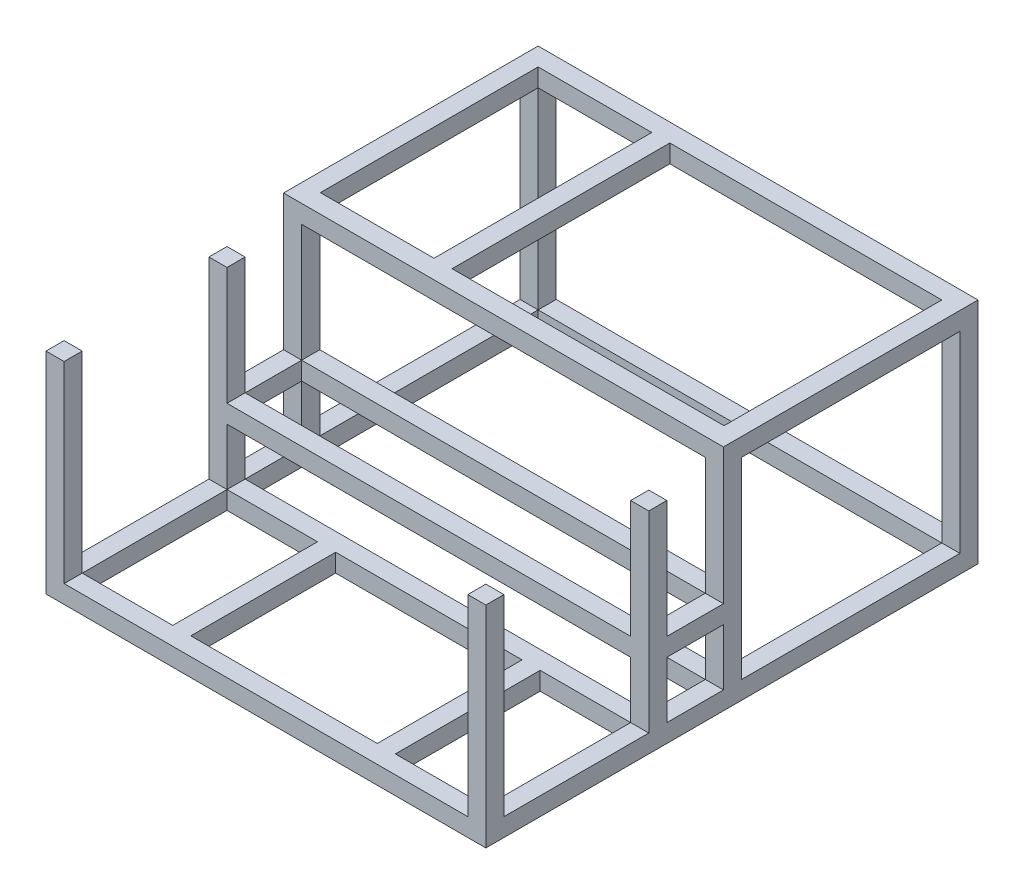
SolidWorks part; units mm, degrees
ref_plane "Front Plane" through (0, 0, 0) normal (0, 0, 1) x (1, 0, 0)
ref_plane "Top Plane" through (0, 0, 0) normal (0, 1, 0) x (1, 0, 0)
ref_plane "Right Plane" through (0, 0, 0) normal (1, 0, 0) x (0, 0, -1)
sketch "Sketch1" plane through (0, 0, 0) normal (1, 0, 0) x (0, 0, -1)
  line L0 (-359.5886, 0) -> (330.9739, 0)
  line L1 (330.9739, 0) -> (330.9739, -320.675)
  line L2 (330.9739, -320.675) -> (-359.5886, -320.675)
  line L3 (-359.5886, -320.675) -> (-359.5886, 0)
  line L4 (-334.1886, -25.4) -> (-334.1886, -295.275)
  line L5 (-334.1886, -295.275) -> (305.5739, -295.275)
  line L6 (305.5739, -295.275) -> (305.5739, -25.4)
  line L7 (305.5739, -25.4) -> (-334.1886, -25.4)
  line L8 (-130.9886, -25.4) -> (-130.9886, -295.275)
  line L9 (-130.9886, -295.275) -> (-105.5886, -295.275)
  line L10 (-105.5886, -295.275) -> (-105.5886, -25.4)
  line L11 (-105.5886, -25.4) -> (-130.9886, -25.4)
  line L12 (-26.2136, -25.4) -> (-26.2136, -295.275)
  line L13 (-26.2136, -295.275) -> (-0.8136, -295.275)
  line L14 (-0.8136, -295.275) -> (-0.8136, -25.4)
  line L15 (-0.8136, -25.4) -> (-26.2136, -25.4)
  line L16 (-105.5886, -190.5) -> (-26.2136, -190.5)
  line L17 (-26.2136, -190.5) -> (-26.2136, -215.9)
  line L18 (-26.2136, -215.9) -> (-105.5886, -215.9)
  line L19 (-105.5886, -215.9) -> (-105.5886, -190.5)
  dimension "D1" = 690.5625
  dimension "D2" = 320.675
  dimension "D3" = 25.4
  dimension "D4" = 25.4
  dimension "D5" = 25.4
  dimension "D6" = 25.4
  dimension "D7" = 25.4
  dimension "D8" = 25.4
  dimension "D9" = 25.4
  dimension "D10" = 254
  dimension "D11" = 358.775
  dimension "D12" = 130.175
extrude "Boss-Extrude1" add sketch "Sketch1" along normal blind 617.22 contours L3 L2 L1 L0 L7 L6 L5 L4 | L5 L14 L7 L12 | L8 L9 L10 L11 | L16 L17 L18 L19
sketch "Sketch2" plane through (0, 0, 359.5886) normal (0, 0, 1) x (1, 0, 0)
  line L0 (25.4, -25.4) -> (25.4, -295.275)
  line L1 (25.4, -295.275) -> (591.82, -295.275)
  line L2 (591.82, -295.275) -> (591.82, -25.4)
  line L3 (591.82, -25.4) -> (25.4, -25.4)
  line L4 (0, -320.675) -> (0, 0) construction
  line L5 (617.22, 0) -> (0, 0) construction
  line L6 (617.22, -320.675) -> (0, -320.675) construction
  line L7 (617.22, -320.675) -> (617.22, 0) construction
  dimension "D1" = 25.4
  dimension "D2" = 25.4
  dimension "D3" = 25.4
  dimension "D4" = 25.4
extrude "Cut-Extrude1" cut sketch "Sketch2" against normal through all
sketch "Sketch3" plane through (0, -190.5, 0) normal (0, 1, 0) x (1, 0, 0)
sketch "Sketch4" plane through (25.4, 0, 0) normal (1, 0, 0) x (0, 0, -1)
  line L0 (-26.2136, -190.5) -> (-0.8136, -190.5)
  line L1 (-0.8136, -295.275) -> (-0.8136, -25.4) construction
  line L2 (-0.8136, -190.5) -> (-0.8136, -215.8777)
  line L3 (-0.8136, -215.8777) -> (-130.9886, -215.8777)
  line L4 (-130.9886, -25.4) -> (-130.9886, -295.275) construction
  line L5 (-130.9886, -215.8777) -> (-130.9886, -190.5)
  line L6 (-130.9886, -190.5) -> (-26.2136, -190.5)
extrude "Boss-Extrude2" add sketch "Sketch4" along normal blind 566.42
sketch "Sketch6" plane through (0, -190.5, 0) normal (0, 1, 0) x (1, 0, 0)
  line L0 (591.82, -105.5886) -> (25.4, -105.5886)
  line L1 (25.4, -105.5886) -> (25.4, -26.2136)
  line L2 (25.4, -26.2136) -> (591.82, -26.2136)
  line L3 (591.82, -26.2136) -> (591.82, -105.5886)
extrude "Cut-Extrude2" cut sketch "Sketch6" against normal up to next
sketch "Sketch7" plane through (0, -295.275, 0) normal (0, 1, 0) x (1, 0, 0)
  line L0 (591.82, -334.1886) -> (591.82, -130.9886)
  line L1 (591.82, -130.9886) -> (464.82, -130.9886)
  line L2 (464.82, -130.9886) -> (464.82, -334.1886)
  line L3 (464.82, -334.1886) -> (591.82, -334.1886)
  line L4 (617.22, -334.1886) -> (617.22, -130.9886) construction
  line L5 (308.61, -359.5886) -> (308.61, 583.7712) construction
  line L6 (25.4, -359.5886) -> (591.82, -359.5886) construction
  line L7 (152.4, -130.9886) -> (152.4, -334.1886)
  line L8 (25.4, -130.9886) -> (152.4, -130.9886)
  line L9 (25.4, -334.1886) -> (25.4, -130.9886)
  line L10 (152.4, -334.1886) -> (25.4, -334.1886)
  line L11 (177.8, -334.1886) -> (177.8, -130.9886)
  line L12 (177.8, -130.9886) -> (439.42, -130.9886)
  line L13 (439.42, -130.9886) -> (439.42, -334.1886)
  line L14 (439.42, -334.1886) -> (177.8, -334.1886)
  dimension "D1" = 152.4
  dimension "D2" = 25.4
  dimension "D3" = 25.4
extrude "Cut-Extrude3" cut sketch "Sketch7" against normal through all
sketch "Sketch8" plane through (0, 0, 0) normal (0, 1, 0) x (1, 0, 0)
  line L0 (591.82, -334.1886) -> (591.82, -26.2136)
  line L1 (591.82, -26.2136) -> (25.4, -26.2136)
  line L2 (25.4, -26.2136) -> (25.4, -334.1886)
  line L3 (25.4, -334.1886) -> (591.82, -334.1886)
  line L4 (617.22, -359.5886) -> (617.22, 330.9739) construction
  line L5 (0, -359.5886) -> (0, 330.9739) construction
  line L6 (617.22, -359.5886) -> (0, -359.5886) construction
  dimension "D1" = 25.4
  dimension "D2" = 25.4
  dimension "D3" = 25.4
  dimension "D4" = 25.4
extrude "Cut-Extrude4" cut sketch "Sketch8" against normal up to next
sketch "Sketch9" plane through (0, 0, 0) normal (0, 1, 0) x (1, 0, 0)
  line L0 (25.4, 305.5739) -> (25.4, 0)
  line L1 (25.4, 0) -> (184.8332, 0)
  line L2 (184.8332, 0) -> (184.8332, 305.5739)
  line L3 (184.8332, 305.5739) -> (25.4, 305.5739)
  line L4 (210.2332, 305.5739) -> (210.2332, 0)
  line L5 (210.2332, 0) -> (591.82, 0)
  line L6 (591.82, 0) -> (591.82, 305.5739)
  line L7 (591.82, 305.5739) -> (210.2332, 305.5739)
  line L8 (0, -359.5886) -> (0, 330.9739) construction
  line L9 (617.22, 330.9739) -> (0, 330.9739) construction
  line L11 (617.22, -359.5886) -> (617.22, 330.9739) construction
  dimension "D1" = 25.4
  dimension "D2" = 25.4
  dimension "D3" = 25.4
  dimension "D4" = 25.4
  dimension "D5" = 25.4
extrude "Cut-Extrude6" cut sketch "Sketch9" against normal up to next
sketch "Sketch10" plane through (0, -295.275, 0) normal (0, 1, 0) x (1, 0, 0)
  line L0 (25.4, 305.5739) -> (591.82, 305.5739)
  line L1 (591.82, 305.5739) -> (591.82, -0.8136)
  line L2 (617.22, -0.8136) -> (591.82, -0.8136) construction
  line L3 (591.82, -0.8136) -> (25.4, -0.8136)
  line L4 (25.4, -0.8136) -> (25.4, 305.5739)
extrude "Cut-Extrude8" cut sketch "Sketch10" against normal up to next
sketch "Sketch12" plane through (0, -295.275, 0) normal (0, 1, 0) x (1, 0, 0)
  line L0 (25.4, -26.2136) -> (591.82, -26.2136)
  line L1 (591.82, -26.2136) -> (591.82, -105.5886)
  line L2 (591.82, -105.5886) -> (25.4, -105.5886)
  line L3 (25.4, -105.5886) -> (25.4, -26.2136)
extrude "Cut-Extrude10" cut sketch "Sketch12" against normal up to next
sketch "Sketch13" plane through (0, 0, 0) normal (0, 1, 0) x (1, 0, 0)
  line L0 (0, -26.2136) -> (0, -359.5886)
  line L1 (0, -359.5886) -> (617.22, -359.5886)
  line L2 (617.22, -359.5886) -> (617.22, -26.2136)
  line L3 (617.22, -26.2136) -> (0, -26.2136)
extrude "Cut-Extrude13" cut sketch "Sketch13" against normal blind 25.4
